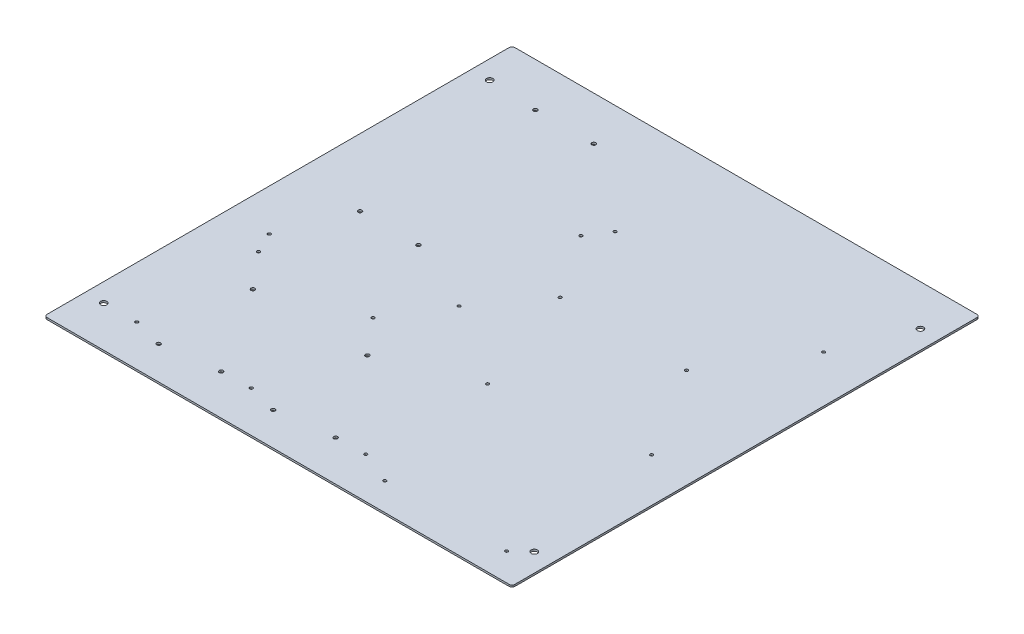
SolidWorks part; units mm, degrees
ref_plane "Front Plane" through (0, 0, 0) normal (0, 0, 1) x (1, 0, 0)
ref_plane "Top Plane" through (0, 0, 0) normal (0, 1, 0) x (1, 0, 0)
ref_plane "Right Plane" through (0, 0, 0) normal (1, 0, 0) x (0, 0, -1)
sketch "Sketch1" plane through (0, 0, 0) normal (0, 1, 0) x (1, 0, 0)
  line L1 (-200.025, 200.025) -> (200.025, 200.025)
  line L2 (-200.025, 200.025) -> (-200.025, -200.025)
  line L3 (-200.025, -200.025) -> (200.025, -200.025)
  line L4 (200.025, 200.025) -> (200.025, -200.025)
  line L5 (-200.025, 200.025) -> (200.025, -200.025) construction
  line L6 (-200.025, -200.025) -> (200.025, 200.025) construction
  point P0 (0, 0)
  dimension "D1" = 400.05
  dimension "D2" = 400.05
extrude "Boss-Extrude1" add sketch "Sketch1" along normal blind 1.5875
sketch "Sketch2" plane through (0, 1.5875, 0) normal (0, 1, 0) x (1, 0, 0)
  line L0 (-203.2, 0) -> (203.2, 0) construction
  line L1 (-203.2, 203.2) -> (203.2, 203.2) construction
  line L2 (-203.2, 203.2) -> (-203.2, -203.2) construction
  line L3 (-203.2, -203.2) -> (203.2, -203.2) construction
  line L4 (203.2, 203.2) -> (203.2, -203.2) construction
  line L5 (-203.2, 203.2) -> (203.2, -203.2) construction
  line L6 (-203.2, -203.2) -> (203.2, 203.2) construction
  line L7 (0, 203.2) -> (0, -203.2) construction
  circle A0 centre (-184.15, -165.1) radius 2.665
  circle A1 centre (184.15, -165.1) radius 2.665
  circle A2 centre (184.15, 165.1) radius 2.665
  circle A3 centre (-184.15, 165.1) radius 2.665
  point P0 (0, 0)
  dimension "D2" = 19.05
  dimension "D3" = 38.1
  dimension "D4" = 5.33
  dimension "D1" = 406.4
extrude "Cut-Extrude1" cut sketch "Sketch2" against normal up to next
fillet "Fillet1" radius 2.54 4 edges at (-200.025, 0.7937, -200.025) (200.025, 0.7937, -200.025) (200.025, 0.7937, 200.025) (-200.025, 0.7937, 200.025)
sketch "Sketch3" plane through (0, 0, 0) normal (0, -1, 0) x (1, 0, 0)
  circle A0 centre (-130.4397, 171.7662) radius 1.665
  circle A1 centre (-83.1864, 165.5581) radius 1.665
  circle A2 centre (-130.5674, 91.046) radius 1.665
  circle A3 centre (-32.5002, 171.7662) radius 1.665
  circle A4 centre (14.753, 165.5581) radius 1.665
  circle A5 centre (-32.628, 91.046) radius 1.665
  dimension "D1" = 3.33
extrude "Cut-Extrude2" cut sketch "Sketch3" against normal up to next
sketch "Sketch4" plane through (0, 1.5875, 0) normal (0, 1, 0) x (1, 0, 0)
  circle A0 centre (-92.525, 12.525) radius 1.1727 construction
  circle A1 centre (-142.525, 12.525) radius 1.1727 construction
  circle A2 centre (-92.525, 162.525) radius 1.1727 construction
  circle A3 centre (-142.525, 162.525) radius 1.1727 construction
  circle A4 centre (-92.525, 12.525) radius 1.1727 construction
  circle A5 centre (-142.525, 12.525) radius 1.1727 construction
  circle A6 centre (-92.525, 162.525) radius 1.1727 construction
  circle A7 centre (-142.525, 162.525) radius 1.1727 construction
  circle A8 centre (-142.525, 162.525) radius 1.665
  circle A9 centre (-92.525, 162.525) radius 1.665
  circle A10 centre (-92.525, 12.525) radius 1.665
  circle A11 centre (-142.525, 12.525) radius 1.665
  dimension "D1" = 3.33
extrude "Cut-Extrude3" cut sketch "Sketch4" against normal up to next
sketch "Sketch5" plane through (0, 1.5875, 0) normal (0, 1, 0) x (1, 0, 0)
  circle A0 centre (114.883, 34.3364) radius 1.27
  circle A1 centre (160.02, 106.5284) radius 1.27
  circle A2 centre (-18.415, 106.5284) radius 1.27
  circle A3 centre (-29.9466, 88.85) radius 1.27
  circle A4 centre (-29.9466, -15.29) radius 1.27
  circle A5 centre (6.883, 34.3364) radius 1.27
  circle A6 centre (-164.465, -43.1284) radius 1.27
  circle A7 centre (-155.9966, -60.8068) radius 1.27
  circle A8 centre (-155.9966, -164.9468) radius 1.27
  circle A9 centre (-58.0571, -164.9468) radius 1.27
  circle A10 centre (39.8823, -164.9468) radius 1.27
  circle A11 centre (67.7207, -176.4784) radius 1.27
  circle A12 centre (171.8607, -176.4784) radius 1.27
  circle A13 centre (39.8823, -60.8068) radius 1.27
  circle A14 centre (-58.0571, -60.8068) radius 1.27
  circle A15 centre (162.56, -43.1284) radius 1.27
  dimension "D1" = 2.54
extrude "Cut-Extrude4" cut sketch "Sketch5" against normal up to next
